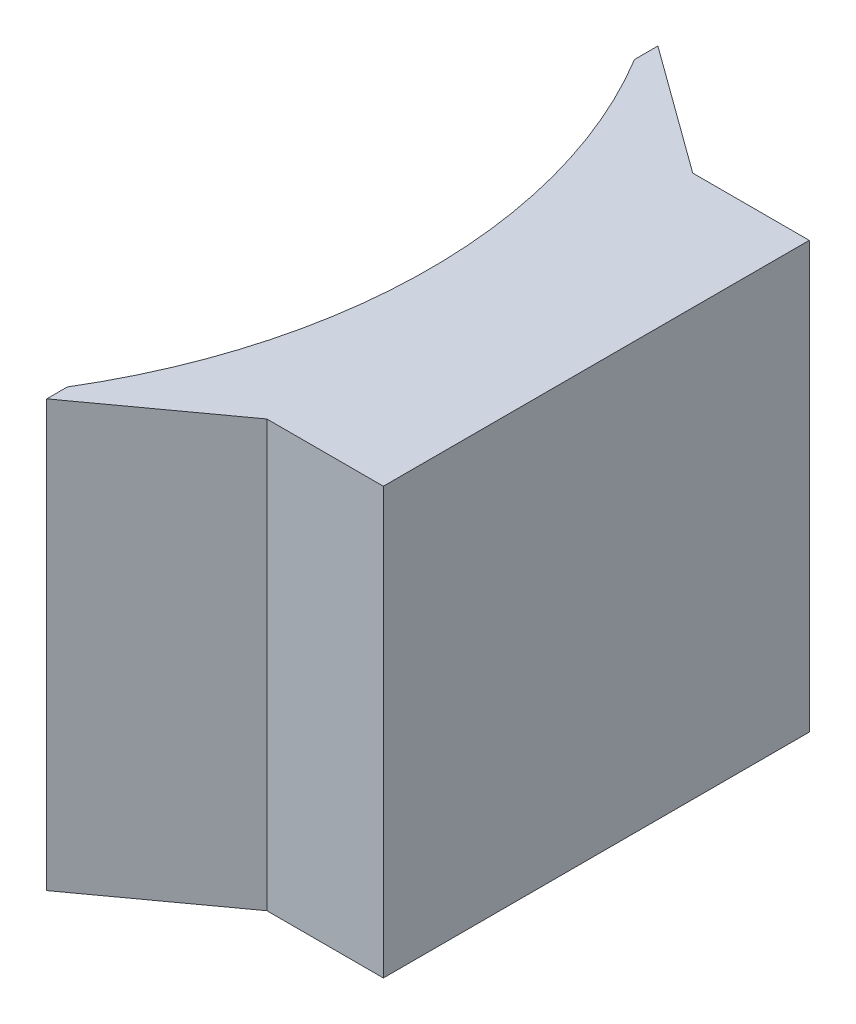
SolidWorks part; units mm, degrees
ref_plane "Front Plane" through (0, 0, 0) normal (0, 0, 1) x (1, 0, 0)
ref_plane "Top Plane" through (0, 0, 0) normal (0, 1, 0) x (1, 0, 0)
ref_plane "Right Plane" through (0, 0, 0) normal (1, 0, 0) x (0, 0, -1)
sketch "Sketch1" plane through (0, 0, 0) normal (1, 0, 0) x (0, 0, -1)
  line L1 (0, 0) -> (-53, 0)
  line L2 (0, 0) -> (0, -53)
  line L3 (0, -53) -> (-53, -53)
  line L4 (-53, 0) -> (-53, -53)
  dimension "D1" = 53
  dimension "D2" = 53
extrude "Boss-Extrude1" add sketch "Sketch1" along normal blind 14.5
sketch "Sketch2" plane through (0, -53, 0) normal (0, -1, 0) x (1, 0, 0)
  line L0 (0, 53) -> (-15.8645, 64.5262)
  line L1 (-15.8645, 64.5262) -> (-15.8645, -11.5262)
  line L2 (-15.8645, -11.5262) -> (0, 0)
  line L3 (14.5, 53) -> (0, 53) construction
  line L4 (14.5, 0) -> (0, 0) construction
  line L9 (0, 53) -> (0, 0)
  line L10 (0, 0) -> (14.5, 0)
  line L11 (14.5, 0) -> (14.5, 53)
  line L12 (14.5, 53) -> (0, 53)
  line L13 (0, 53) -> (0, 0)
  dimension "D1" = 144
  dimension "D2" = 144
  dimension "D3" = 0
extrude "Boss-Extrude2" add sketch "Sketch2" against normal blind 53 contours L1 L2 L13 L0
sketch "Sketch5" plane through (0, 0, 0) normal (0, 1, 0) x (1, 0, 0)
  circle A0 centre (-74.3525, -26.67) radius 68.3112
extrude "Cut-Extrude1" cut sketch "Sketch5" against normal blind 60
scale "Scale1" bodies to scale 103 scale about origin uniform scaling yes scale factor 4
